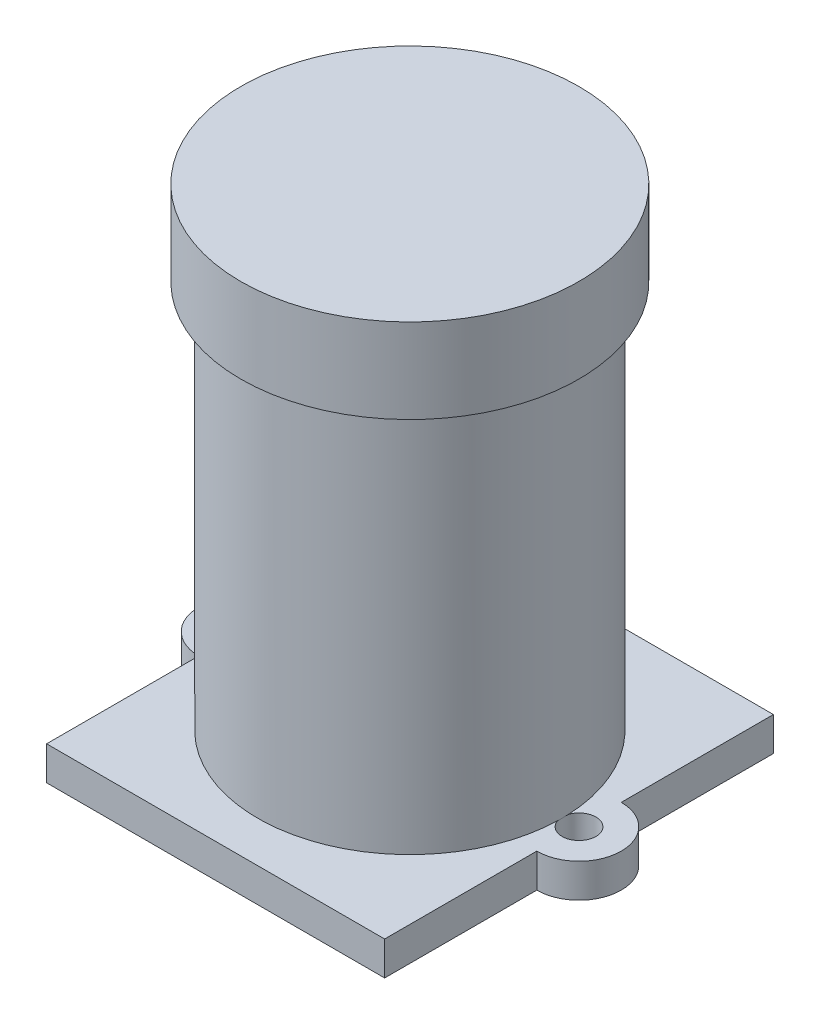
SolidWorks part; units mm, degrees
ref_plane "前视基准面" through (0, 0, 0) normal (0, 0, 1) x (1, 0, 0)
ref_plane "上视基准面" through (0, 0, 0) normal (0, 1, 0) x (1, 0, 0)
ref_plane "右视基准面" through (0, 0, 0) normal (1, 0, 0) x (0, 0, -1)
sketch "草图1" plane through (0, 0, 0) normal (0, 1, 0) x (1, 0, 0)
  line L0 (0, -11.5) -> (20, -11.5) construction
  line L1 (0, 0) -> (20, 0)
  line L2 (0, 0) -> (0, -23)
  line L3 (0, -23) -> (20, -23)
  line L4 (20, 0) -> (20, -23)
  circle A0 centre (0, -11.5) radius 1
  circle A1 centre (20, -11.5) radius 1
  circle A2 centre (0, -11.5) radius 2.5
  circle A3 centre (20, -11.5) radius 2.5
  point P13 (0, 0)
  point P14 (0, 0)
  dimension "D3" = 2
  dimension "D4" = 5
  dimension "D5" = 2
  dimension "D6" = 5
  dimension "D1" = 20
  dimension "D2" = 23
extrude "凸台-拉伸1" add sketch "草图1" along normal blind 2 contours L0 A2 L2 L3 L4 A3 | A2 L0 A3 L4 L1 L2 | A0 L0 A2 L2 | L0 A0 L2 A2 | L2 A2 A0 | A3 L0 A1 L4 | L0 A3 L4 A1 | L4 A3 A1
sketch "草图2" plane through (0, 2, 0) normal (0, 1, 0) x (1, 0, 0)
  line L0 (0, 0) -> (20, -23) construction
  line L1 (20, 0) -> (0, -23) construction
  circle A0 centre (10.0622, -11.5715) radius 9
  dimension "D1" = 18
extrude "凸台-拉伸2" add sketch "草图2" along normal blind 23
sketch "草图4" plane through (0, 25, 0) normal (0, 1, 0) x (1, 0, 0)
  circle A0 centre (10.0622, -11.5715) radius 10
  dimension "D1" = 20
extrude "凸台-拉伸3" add sketch "草图4" along normal blind 5
